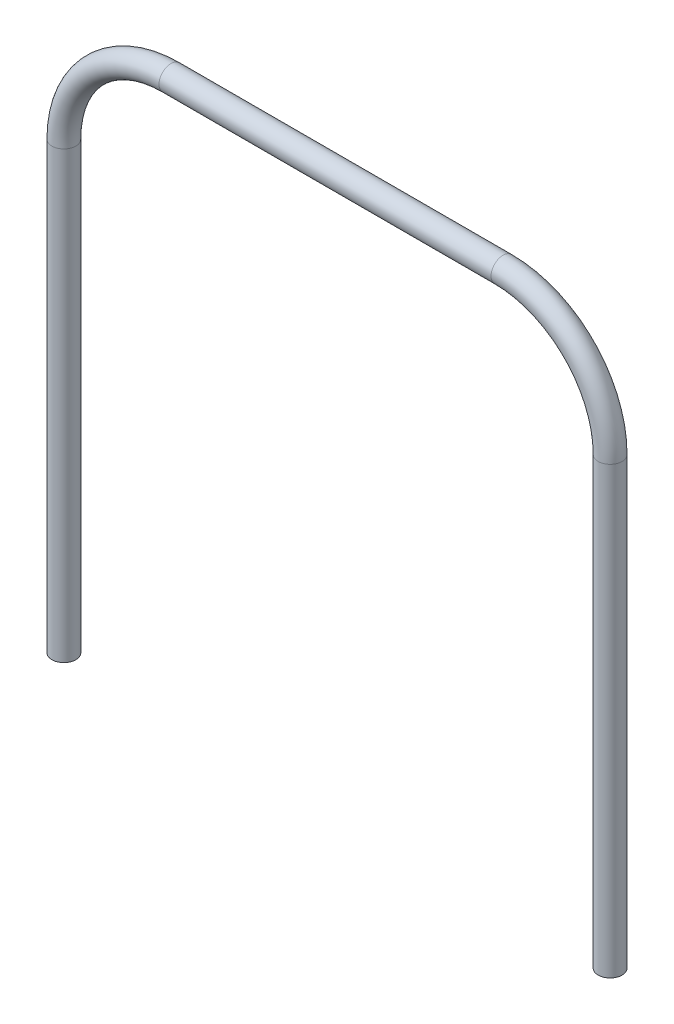
SolidWorks part; units mm, degrees
ref_plane "Front Plane" through (0, 0, 0) normal (0, 0, 1) x (1, 0, 0)
ref_plane "Top Plane" through (0, 0, 0) normal (0, 1, 0) x (1, 0, 0)
ref_plane "Right Plane" through (0, 0, 0) normal (1, 0, 0) x (0, 0, -1)
sketch "Sketch1" plane through (0, 0, 0) normal (0, 0, 1) x (1, 0, 0)
  line L0 (0, 0) -> (0, 706)
  line L1 (170, 876) -> (697, 876)
  line L2 (867, 706) -> (867, 0)
  arc A0 (867, 706) -> (697, 876) centre (697, 706) ccw
  arc A1 (170, 876) -> (0, 706) centre (170, 706) ccw
  point P7 (867, 876)
  point P10 (0, 876)
  dimension "D3" = 170
  dimension "D1" = 876
  dimension "D2" = 867
sketch "Sketch2" plane through (0, 0, 0) normal (0, 1, 0) x (1, 0, 0)
  circle A0 centre (0, 0) radius 19
  circle A1 centre (0, 0) radius 17.8
  dimension "D1" = 38
  dimension "D2" = 1.2
sweep "Sweep1" add profiles "Sketch2" path "Sketch1"
